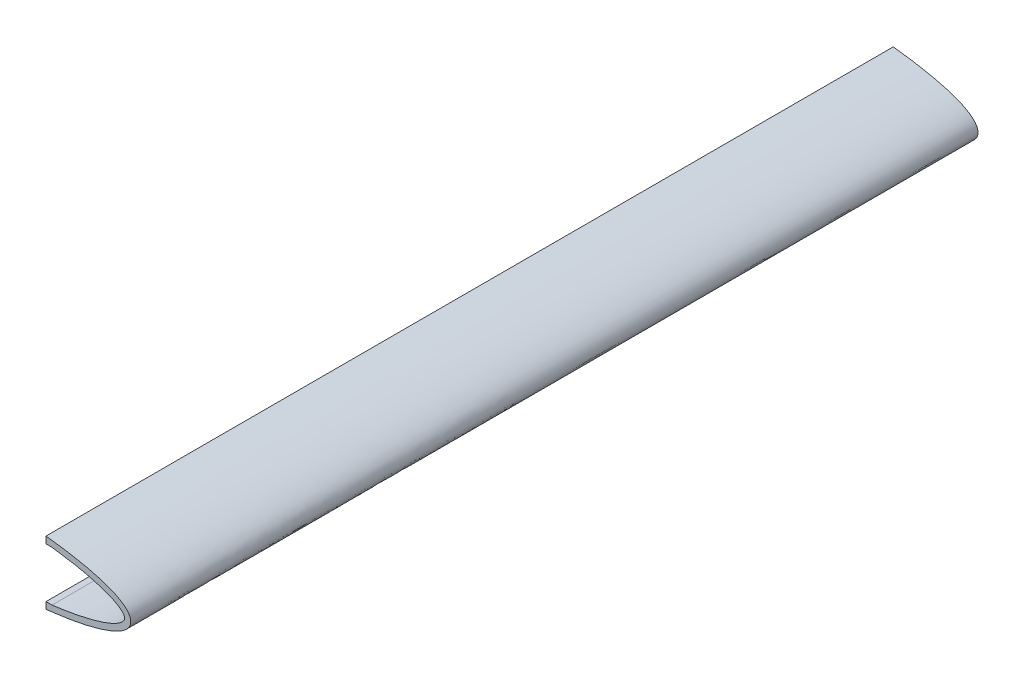
SolidWorks part; units mm, degrees
material "Balsa"
ref_plane "Front Plane" through (0, 0, 0) normal (0, 0, 1) x (1, 0, 0)
ref_plane "Top Plane" through (0, 0, 0) normal (0, 1, 0) x (1, 0, 0)
ref_plane "Right Plane" through (0, 0, 0) normal (1, 0, 0) x (0, 0, -1)
sketch "Sketch1" plane through (0, 0, 0) normal (0, 0, 1) x (1, 0, 0)
  line L0 (0, 29.7752) -> (0, 33.354)
  line L1 (0, 3.5788) -> (0, 0)
  line L4 (3.175, 3.5788) -> (0, 3.5788)
  line L5 (3.175, 29.7752) -> (0, 29.7752)
  line L6 (0, 16.677) -> (0, 33.354) construction
  line L7 (3.175, 16.677) -> (3.175, 29.7752) construction
  line L8 (3.175, 16.677) -> (3.175, 3.5788) construction
  line L9 (0, 16.677) -> (0, 0) construction
  spline S1 degree 3 poles (0, 0) (2.0904, 0.2369) (6.7725, 0.8206) (13.7716, 1.9045) (20.72, 3.2719) (26.8369, 4.7927) (32.0876, 6.4522) (36.4453, 8.2347) (39.8961, 10.1284) (42.4348, 12.1369) (44.0608, 14.3087) (44.6314, 16.677) (44.0608, 19.0452) (42.4348, 21.2171) (39.8961, 23.2256) (36.4453, 25.1192) (32.0876, 26.9018) (26.8369, 28.5612) (20.72, 30.082) (13.7716, 31.4494) (6.7725, 32.5333) (2.0904, 33.117) (0, 33.354) knots 0.42433 0.42433 0.42433 0.42433 0.434028 0.446078 0.456972 0.466663 0.475121 0.482336 0.488336 0.49321 0.497165 0.500617 0.504069 0.508025 0.512898 0.518898 0.526114 0.534571 0.544262 0.555156 0.567207 0.576905 0.576905 0.576905 0.576905
  spline S2 degree 1 poles (3.175, 3.5788) (3.175, 29.7752) knots 0 0 1 1 construction
  spline S3 degree 3 poles (3.175, 3.5788) (6.9245, 4.0547) (14.4227, 5.1763) (23.6015, 7.1509) (29.7887, 9.0374) (33.1794, 10.3208) (35.6148, 11.4119) (37.8612, 12.6506) (39.793, 14.053) (40.8823, 15.3315) (41.1768, 16.0344) (41.2632, 16.4305) (41.2809, 16.677) (41.2632, 16.9235) (41.1768, 17.3196) (40.8823, 18.0224) (39.793, 19.3009) (37.8612, 20.7033) (35.6148, 21.9421) (33.1794, 23.0332) (29.7887, 24.3166) (23.6015, 26.203) (14.4227, 28.1777) (6.9245, 29.2992) (3.175, 29.7752) knots 0.429862 0.429862 0.429862 0.429862 0.447551 0.46524 0.474084 0.478506 0.482928 0.487351 0.491773 0.496195 0.498406 0.499512 0.500617 0.501723 0.502828 0.505039 0.509462 0.513884 0.518306 0.522728 0.52715 0.535995 0.553683 0.571372 0.571372 0.571372 0.571372
  dimension "D1" = 3.175
extrude "Boss-Extrude1" add sketch "Sketch1" along normal blind 444.5
